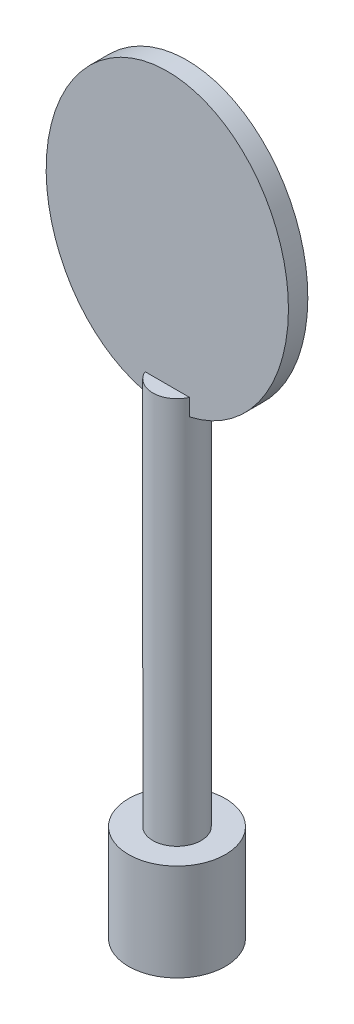
SolidWorks part; units mm, degrees
ref_plane "前视基准面" through (0, 0, 0) normal (0, 0, 1) x (1, 0, 0)
ref_plane "上视基准面" through (0, 0, 0) normal (0, 1, 0) x (1, 0, 0)
ref_plane "右视基准面" through (0, 0, 0) normal (1, 0, 0) x (0, 0, -1)
sketch "草图1" plane through (0, 0, 0) normal (0, 1, 0) x (1, 0, 0)
  circle A0 centre (0, 0) radius 50
  dimension "D1" = 100
extrude "凸台-拉伸1" add sketch "草图1" along normal blind 100
sketch "草图2" plane through (0, 100, 0) normal (0, 1, 0) x (1, 0, 0)
  circle A0 centre (0, 0) radius 25
  dimension "D1" = 50
extrude "凸台-拉伸2" add sketch "草图2" along normal blind 400
sketch "草图3" plane through (0, 0, 0) normal (0, 0, 1) x (1, 0, 0)
  line L0 (25, 500) -> (-25, 500) construction
  ellipse E0 centre (0, 630) end of major axis (0, 780) minor radius 125
  dimension "D1" = 250
  dimension "D2" = 300
  dimension "D3" = 130
extrude "凸台-拉伸3" add sketch "草图3" along normal mid plane 20 contours E0
sketch "草图4" plane through (0, 0, 0) normal (0, 0, 1) x (1, 0, 0)
  ellipse E0 centre (0, 630) end of major axis (0, 780) minor radius 125 (22.9129, 482.5415) -> (-22.9129, 482.5415) ccw construction
  point P0 (0, 630)
  dimension "D1" = 0
